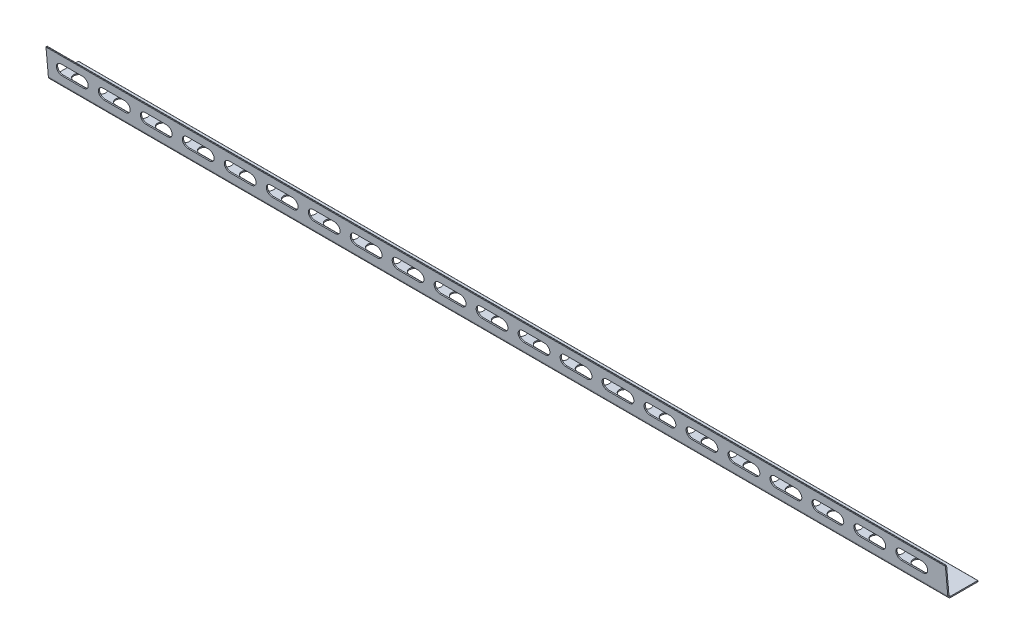
SolidWorks part; units mm, degrees
ref_plane "前视基准面" through (0, 0, 0) normal (0, 0, 1) x (1, 0, 0)
ref_plane "上视基准面" through (0, 0, 0) normal (0, 1, 0) x (1, 0, 0)
ref_plane "右视基准面" through (0, 0, 0) normal (1, 0, 0) x (0, 0, -1)
other "Configuration Table"
sketch "草图1" plane through (0, 0, 0) normal (1, 0, 0) x (0, 0, -1)
  line L0 (-0.5, 0) -> (-45.4183, 0)
  line L1 (-50.3993, 4.5642) -> (-54.3142, 49.3116)
  line L2 (-0.5, 2) -> (-45.4183, 2)
  line L3 (-48.4069, 4.7385) -> (-52.3218, 49.4859)
  line L4 (-53.8597, 49.8533) -> (-52.8635, 49.9405)
  line L5 (-48.4069, 4.7385) -> (-52.3654, 49.984) construction
  line L6 (-50.3993, 4.5642) -> (-54.3578, 49.8097) construction
  line L7 (0, 0.5) -> (0, 1.5)
  line L8 (0, 0) -> (-45.4183, 0) construction
  line L9 (0, 2) -> (-45.4183, 2) construction
  arc A0 (-50.3993, 4.5642) -> (-45.4183, 0) centre (-45.4183, 5) ccw
  arc A1 (-48.4069, 4.7385) -> (-45.4183, 2) centre (-45.4183, 5) ccw
  arc A2 (-52.8635, 49.9405) -> (-52.3218, 49.4859) centre (-52.8199, 49.4424) cw
  arc A3 (-53.8597, 49.8533) -> (-54.3142, 49.3116) centre (-53.8161, 49.3552) ccw
  arc A4 (0, 0.5) -> (-0.5, 0) centre (-0.5, 0.5) cw
  arc A5 (0, 1.5) -> (-0.5, 2) centre (-0.5, 1.5) ccw
  point P6 (-50, 0)
  point P18 (-54.3578, 49.8097)
  point P22 (0, 0)
  dimension "D4" = 5
  dimension "D6" = 0.5
  dimension "D7" = 0.5
  dimension "D1" = 50
  dimension "D2" = 50
  dimension "D3" = 95
  dimension "D5" = 2
extrude "凸台-拉伸1" add sketch "草图1" along normal blind 1500
sketch "草图2" plane through (0, 2, 0) normal (0, 1, 0) x (1, 0, 0)
  line L0 (24.5, -23.5) -> (59.5, -23.5) construction
  line L1 (24.5, -14.5) -> (59.5, -14.5)
  line L2 (24.5, -32.5) -> (59.5, -32.5)
  line L3 (0, -0.5) -> (0, -45.4183) construction
  line L4 (1500, -0.5) -> (0, -0.5) construction
  line L5 (94.5, -23.5) -> (129.5, -23.5) construction
  line L6 (94.5, -14.5) -> (129.5, -14.5)
  line L7 (94.5, -32.5) -> (129.5, -32.5)
  line L8 (164.5, -23.5) -> (199.5, -23.5) construction
  line L9 (164.5, -14.5) -> (199.5, -14.5)
  line L10 (164.5, -32.5) -> (199.5, -32.5)
  line L11 (234.5, -23.5) -> (269.5, -23.5) construction
  line L12 (234.5, -14.5) -> (269.5, -14.5)
  line L13 (234.5, -32.5) -> (269.5, -32.5)
  line L14 (304.5, -23.5) -> (339.5, -23.5) construction
  line L15 (304.5, -14.5) -> (339.5, -14.5)
  line L16 (304.5, -32.5) -> (339.5, -32.5)
  line L17 (374.5, -23.5) -> (409.5, -23.5) construction
  line L18 (374.5, -14.5) -> (409.5, -14.5)
  line L19 (374.5, -32.5) -> (409.5, -32.5)
  line L20 (444.5, -23.5) -> (479.5, -23.5) construction
  line L21 (444.5, -14.5) -> (479.5, -14.5)
  line L22 (444.5, -32.5) -> (479.5, -32.5)
  line L23 (514.5, -23.5) -> (549.5, -23.5) construction
  line L24 (514.5, -14.5) -> (549.5, -14.5)
  line L25 (514.5, -32.5) -> (549.5, -32.5)
  line L26 (584.5, -23.5) -> (619.5, -23.5) construction
  line L27 (584.5, -14.5) -> (619.5, -14.5)
  line L28 (584.5, -32.5) -> (619.5, -32.5)
  line L29 (654.5, -23.5) -> (689.5, -23.5) construction
  line L30 (654.5, -14.5) -> (689.5, -14.5)
  line L31 (654.5, -32.5) -> (689.5, -32.5)
  line L32 (724.5, -23.5) -> (759.5, -23.5) construction
  line L33 (724.5, -14.5) -> (759.5, -14.5)
  line L34 (724.5, -32.5) -> (759.5, -32.5)
  line L35 (794.5, -23.5) -> (829.5, -23.5) construction
  line L36 (794.5, -14.5) -> (829.5, -14.5)
  line L37 (794.5, -32.5) -> (829.5, -32.5)
  line L38 (864.5, -23.5) -> (899.5, -23.5) construction
  line L39 (864.5, -14.5) -> (899.5, -14.5)
  line L40 (864.5, -32.5) -> (899.5, -32.5)
  line L41 (934.5, -23.5) -> (969.5, -23.5) construction
  line L42 (934.5, -14.5) -> (969.5, -14.5)
  line L43 (934.5, -32.5) -> (969.5, -32.5)
  line L44 (1004.5, -23.5) -> (1039.5, -23.5) construction
  line L45 (1004.5, -14.5) -> (1039.5, -14.5)
  line L46 (1004.5, -32.5) -> (1039.5, -32.5)
  line L47 (1074.5, -23.5) -> (1109.5, -23.5) construction
  line L48 (1074.5, -14.5) -> (1109.5, -14.5)
  line L49 (1074.5, -32.5) -> (1109.5, -32.5)
  line L50 (1144.5, -23.5) -> (1179.5, -23.5) construction
  line L51 (1144.5, -14.5) -> (1179.5, -14.5)
  line L52 (1144.5, -32.5) -> (1179.5, -32.5)
  line L53 (1214.5, -23.5) -> (1249.5, -23.5) construction
  line L54 (1214.5, -14.5) -> (1249.5, -14.5)
  line L55 (1214.5, -32.5) -> (1249.5, -32.5)
  line L56 (1284.5, -23.5) -> (1319.5, -23.5) construction
  line L57 (1284.5, -14.5) -> (1319.5, -14.5)
  line L58 (1284.5, -32.5) -> (1319.5, -32.5)
  line L59 (1354.5, -23.5) -> (1389.5, -23.5) construction
  line L60 (1354.5, -14.5) -> (1389.5, -14.5)
  line L61 (1354.5, -32.5) -> (1389.5, -32.5)
  line L62 (1424.5, -23.5) -> (1459.5, -23.5) construction
  line L63 (1424.5, -14.5) -> (1459.5, -14.5)
  line L64 (1424.5, -32.5) -> (1459.5, -32.5)
  line L65 (0, -45.4183) -> (0, -53.1914)
  arc A0 (24.5, -14.5) -> (24.5, -32.5) centre (24.5, -23.5) ccw
  arc A1 (59.5, -32.5) -> (59.5, -14.5) centre (59.5, -23.5) ccw
  arc A2 (94.5, -14.5) -> (94.5, -32.5) centre (94.5, -23.5) ccw
  arc A3 (129.5, -32.5) -> (129.5, -14.5) centre (129.5, -23.5) ccw
  arc A4 (164.5, -14.5) -> (164.5, -32.5) centre (164.5, -23.5) ccw
  arc A5 (199.5, -32.5) -> (199.5, -14.5) centre (199.5, -23.5) ccw
  arc A6 (234.5, -14.5) -> (234.5, -32.5) centre (234.5, -23.5) ccw
  arc A7 (269.5, -32.5) -> (269.5, -14.5) centre (269.5, -23.5) ccw
  arc A8 (304.5, -14.5) -> (304.5, -32.5) centre (304.5, -23.5) ccw
  arc A9 (339.5, -32.5) -> (339.5, -14.5) centre (339.5, -23.5) ccw
  arc A10 (374.5, -14.5) -> (374.5, -32.5) centre (374.5, -23.5) ccw
  arc A11 (409.5, -32.5) -> (409.5, -14.5) centre (409.5, -23.5) ccw
  arc A12 (444.5, -14.5) -> (444.5, -32.5) centre (444.5, -23.5) ccw
  arc A13 (479.5, -32.5) -> (479.5, -14.5) centre (479.5, -23.5) ccw
  arc A14 (514.5, -14.5) -> (514.5, -32.5) centre (514.5, -23.5) ccw
  arc A15 (549.5, -32.5) -> (549.5, -14.5) centre (549.5, -23.5) ccw
  arc A16 (584.5, -14.5) -> (584.5, -32.5) centre (584.5, -23.5) ccw
  arc A17 (619.5, -32.5) -> (619.5, -14.5) centre (619.5, -23.5) ccw
  arc A18 (654.5, -14.5) -> (654.5, -32.5) centre (654.5, -23.5) ccw
  arc A19 (689.5, -32.5) -> (689.5, -14.5) centre (689.5, -23.5) ccw
  arc A20 (724.5, -14.5) -> (724.5, -32.5) centre (724.5, -23.5) ccw
  arc A21 (759.5, -32.5) -> (759.5, -14.5) centre (759.5, -23.5) ccw
  arc A22 (794.5, -14.5) -> (794.5, -32.5) centre (794.5, -23.5) ccw
  arc A23 (829.5, -32.5) -> (829.5, -14.5) centre (829.5, -23.5) ccw
  arc A24 (864.5, -14.5) -> (864.5, -32.5) centre (864.5, -23.5) ccw
  arc A25 (899.5, -32.5) -> (899.5, -14.5) centre (899.5, -23.5) ccw
  arc A26 (934.5, -14.5) -> (934.5, -32.5) centre (934.5, -23.5) ccw
  arc A27 (969.5, -32.5) -> (969.5, -14.5) centre (969.5, -23.5) ccw
  arc A28 (1004.5, -14.5) -> (1004.5, -32.5) centre (1004.5, -23.5) ccw
  arc A29 (1039.5, -32.5) -> (1039.5, -14.5) centre (1039.5, -23.5) ccw
  arc A30 (1074.5, -14.5) -> (1074.5, -32.5) centre (1074.5, -23.5) ccw
  arc A31 (1109.5, -32.5) -> (1109.5, -14.5) centre (1109.5, -23.5) ccw
  arc A32 (1144.5, -14.5) -> (1144.5, -32.5) centre (1144.5, -23.5) ccw
  arc A33 (1179.5, -32.5) -> (1179.5, -14.5) centre (1179.5, -23.5) ccw
  arc A34 (1214.5, -14.5) -> (1214.5, -32.5) centre (1214.5, -23.5) ccw
  arc A35 (1249.5, -32.5) -> (1249.5, -14.5) centre (1249.5, -23.5) ccw
  arc A36 (1284.5, -14.5) -> (1284.5, -32.5) centre (1284.5, -23.5) ccw
  arc A37 (1319.5, -32.5) -> (1319.5, -14.5) centre (1319.5, -23.5) ccw
  arc A38 (1354.5, -14.5) -> (1354.5, -32.5) centre (1354.5, -23.5) ccw
  arc A39 (1389.5, -32.5) -> (1389.5, -14.5) centre (1389.5, -23.5) ccw
  arc A40 (1424.5, -14.5) -> (1424.5, -32.5) centre (1424.5, -23.5) ccw
  arc A41 (1459.5, -32.5) -> (1459.5, -14.5) centre (1459.5, -23.5) ccw
  point P2 (42, -23.5)
  point P9 (0, -22.9592)
  point P15 (112, -23.5)
  point P22 (182, -23.5)
  point P29 (252, -23.5)
  point P36 (322, -23.5)
  point P43 (392, -23.5)
  point P50 (462, -23.5)
  point P57 (532, -23.5)
  point P64 (602, -23.5)
  point P71 (672, -23.5)
  point P78 (742, -23.5)
  point P85 (812, -23.5)
  point P92 (882, -23.5)
  point P99 (952, -23.5)
  point P106 (1022, -23.5)
  point P113 (1092, -23.5)
  point P120 (1162, -23.5)
  point P127 (1232, -23.5)
  point P134 (1302, -23.5)
  point P141 (1372, -23.5)
  point P148 (1442, -23.5)
  dimension "D1" = 24.5
  dimension "D4" = 14
  dimension "D2" = 9
  dimension "D3" = 35
  dimension "D5" = 21
sketch "草图3" plane through (0, -4.1669, 47.6278) normal (0, 0.0872, -0.9962) x (-1, 0, 0)
  line L0 (-59.5, 31.9394) -> (-24.5, 31.9394) construction
  line L1 (-59.5, 40.9394) -> (-24.5, 40.9394)
  line L2 (-59.5, 22.9394) -> (-24.5, 22.9394)
  line L3 (0, 8.9394) -> (0, 53.8578) construction
  line L4 (-1500, 8.9394) -> (0, 8.9394) construction
  line L5 (-129.5, 31.9394) -> (-94.5, 31.9394) construction
  line L6 (-129.5, 40.9394) -> (-94.5, 40.9394)
  line L7 (-129.5, 22.9394) -> (-94.5, 22.9394)
  line L8 (-199.5, 31.9394) -> (-164.5, 31.9394) construction
  line L9 (-199.5, 40.9394) -> (-164.5, 40.9394)
  line L10 (-199.5, 22.9394) -> (-164.5, 22.9394)
  line L11 (-269.5, 31.9394) -> (-234.5, 31.9394) construction
  line L12 (-269.5, 40.9394) -> (-234.5, 40.9394)
  line L13 (-269.5, 22.9394) -> (-234.5, 22.9394)
  line L14 (-339.5, 31.9394) -> (-304.5, 31.9394) construction
  line L15 (-339.5, 40.9394) -> (-304.5, 40.9394)
  line L16 (-339.5, 22.9394) -> (-304.5, 22.9394)
  line L17 (-409.5, 31.9394) -> (-374.5, 31.9394) construction
  line L18 (-409.5, 40.9394) -> (-374.5, 40.9394)
  line L19 (-409.5, 22.9394) -> (-374.5, 22.9394)
  line L20 (-479.5, 31.9394) -> (-444.5, 31.9394) construction
  line L21 (-479.5, 40.9394) -> (-444.5, 40.9394)
  line L22 (-479.5, 22.9394) -> (-444.5, 22.9394)
  line L23 (-549.5, 31.9394) -> (-514.5, 31.9394) construction
  line L24 (-549.5, 40.9394) -> (-514.5, 40.9394)
  line L25 (-549.5, 22.9394) -> (-514.5, 22.9394)
  line L26 (-619.5, 31.9394) -> (-584.5, 31.9394) construction
  line L27 (-619.5, 40.9394) -> (-584.5, 40.9394)
  line L28 (-619.5, 22.9394) -> (-584.5, 22.9394)
  line L29 (-689.5, 31.9394) -> (-654.5, 31.9394) construction
  line L30 (-689.5, 40.9394) -> (-654.5, 40.9394)
  line L31 (-689.5, 22.9394) -> (-654.5, 22.9394)
  line L32 (-759.5, 31.9394) -> (-724.5, 31.9394) construction
  line L33 (-759.5, 40.9394) -> (-724.5, 40.9394)
  line L34 (-759.5, 22.9394) -> (-724.5, 22.9394)
  line L35 (-829.5, 31.9394) -> (-794.5, 31.9394) construction
  line L36 (-829.5, 40.9394) -> (-794.5, 40.9394)
  line L37 (-829.5, 22.9394) -> (-794.5, 22.9394)
  line L38 (-899.5, 31.9394) -> (-864.5, 31.9394) construction
  line L39 (-899.5, 40.9394) -> (-864.5, 40.9394)
  line L40 (-899.5, 22.9394) -> (-864.5, 22.9394)
  line L41 (-969.5, 31.9394) -> (-934.5, 31.9394) construction
  line L42 (-969.5, 40.9394) -> (-934.5, 40.9394)
  line L43 (-969.5, 22.9394) -> (-934.5, 22.9394)
  line L44 (-1039.5, 31.9394) -> (-1004.5, 31.9394) construction
  line L45 (-1039.5, 40.9394) -> (-1004.5, 40.9394)
  line L46 (-1039.5, 22.9394) -> (-1004.5, 22.9394)
  line L47 (-1109.5, 31.9394) -> (-1074.5, 31.9394) construction
  line L48 (-1109.5, 40.9394) -> (-1074.5, 40.9394)
  line L49 (-1109.5, 22.9394) -> (-1074.5, 22.9394)
  line L50 (-1179.5, 31.9394) -> (-1144.5, 31.9394) construction
  line L51 (-1179.5, 40.9394) -> (-1144.5, 40.9394)
  line L52 (-1179.5, 22.9394) -> (-1144.5, 22.9394)
  line L53 (-1249.5, 31.9394) -> (-1214.5, 31.9394) construction
  line L54 (-1249.5, 40.9394) -> (-1214.5, 40.9394)
  line L55 (-1249.5, 22.9394) -> (-1214.5, 22.9394)
  line L56 (-1319.5, 31.9394) -> (-1284.5, 31.9394) construction
  line L57 (-1319.5, 40.9394) -> (-1284.5, 40.9394)
  line L58 (-1319.5, 22.9394) -> (-1284.5, 22.9394)
  line L59 (-1389.5, 31.9394) -> (-1354.5, 31.9394) construction
  line L60 (-1389.5, 40.9394) -> (-1354.5, 40.9394)
  line L61 (-1389.5, 22.9394) -> (-1354.5, 22.9394)
  line L62 (-1459.5, 31.9394) -> (-1424.5, 31.9394) construction
  line L63 (-1459.5, 40.9394) -> (-1424.5, 40.9394)
  line L64 (-1459.5, 22.9394) -> (-1424.5, 22.9394)
  arc A0 (-59.5, 40.9394) -> (-59.5, 22.9394) centre (-59.5, 31.9394) ccw
  arc A1 (-24.5, 22.9394) -> (-24.5, 40.9394) centre (-24.5, 31.9394) ccw
  arc A2 (-129.5, 40.9394) -> (-129.5, 22.9394) centre (-129.5, 31.9394) ccw
  arc A3 (-94.5, 22.9394) -> (-94.5, 40.9394) centre (-94.5, 31.9394) ccw
  arc A4 (-199.5, 40.9394) -> (-199.5, 22.9394) centre (-199.5, 31.9394) ccw
  arc A5 (-164.5, 22.9394) -> (-164.5, 40.9394) centre (-164.5, 31.9394) ccw
  arc A6 (-269.5, 40.9394) -> (-269.5, 22.9394) centre (-269.5, 31.9394) ccw
  arc A7 (-234.5, 22.9394) -> (-234.5, 40.9394) centre (-234.5, 31.9394) ccw
  arc A8 (-339.5, 40.9394) -> (-339.5, 22.9394) centre (-339.5, 31.9394) ccw
  arc A9 (-304.5, 22.9394) -> (-304.5, 40.9394) centre (-304.5, 31.9394) ccw
  arc A10 (-409.5, 40.9394) -> (-409.5, 22.9394) centre (-409.5, 31.9394) ccw
  arc A11 (-374.5, 22.9394) -> (-374.5, 40.9394) centre (-374.5, 31.9394) ccw
  arc A12 (-479.5, 40.9394) -> (-479.5, 22.9394) centre (-479.5, 31.9394) ccw
  arc A13 (-444.5, 22.9394) -> (-444.5, 40.9394) centre (-444.5, 31.9394) ccw
  arc A14 (-549.5, 40.9394) -> (-549.5, 22.9394) centre (-549.5, 31.9394) ccw
  arc A15 (-514.5, 22.9394) -> (-514.5, 40.9394) centre (-514.5, 31.9394) ccw
  arc A16 (-619.5, 40.9394) -> (-619.5, 22.9394) centre (-619.5, 31.9394) ccw
  arc A17 (-584.5, 22.9394) -> (-584.5, 40.9394) centre (-584.5, 31.9394) ccw
  arc A18 (-689.5, 40.9394) -> (-689.5, 22.9394) centre (-689.5, 31.9394) ccw
  arc A19 (-654.5, 22.9394) -> (-654.5, 40.9394) centre (-654.5, 31.9394) ccw
  arc A20 (-759.5, 40.9394) -> (-759.5, 22.9394) centre (-759.5, 31.9394) ccw
  arc A21 (-724.5, 22.9394) -> (-724.5, 40.9394) centre (-724.5, 31.9394) ccw
  arc A22 (-829.5, 40.9394) -> (-829.5, 22.9394) centre (-829.5, 31.9394) ccw
  arc A23 (-794.5, 22.9394) -> (-794.5, 40.9394) centre (-794.5, 31.9394) ccw
  arc A24 (-899.5, 40.9394) -> (-899.5, 22.9394) centre (-899.5, 31.9394) ccw
  arc A25 (-864.5, 22.9394) -> (-864.5, 40.9394) centre (-864.5, 31.9394) ccw
  arc A26 (-969.5, 40.9394) -> (-969.5, 22.9394) centre (-969.5, 31.9394) ccw
  arc A27 (-934.5, 22.9394) -> (-934.5, 40.9394) centre (-934.5, 31.9394) ccw
  arc A28 (-1039.5, 40.9394) -> (-1039.5, 22.9394) centre (-1039.5, 31.9394) ccw
  arc A29 (-1004.5, 22.9394) -> (-1004.5, 40.9394) centre (-1004.5, 31.9394) ccw
  arc A30 (-1109.5, 40.9394) -> (-1109.5, 22.9394) centre (-1109.5, 31.9394) ccw
  arc A31 (-1074.5, 22.9394) -> (-1074.5, 40.9394) centre (-1074.5, 31.9394) ccw
  arc A32 (-1179.5, 40.9394) -> (-1179.5, 22.9394) centre (-1179.5, 31.9394) ccw
  arc A33 (-1144.5, 22.9394) -> (-1144.5, 40.9394) centre (-1144.5, 31.9394) ccw
  arc A34 (-1249.5, 40.9394) -> (-1249.5, 22.9394) centre (-1249.5, 31.9394) ccw
  arc A35 (-1214.5, 22.9394) -> (-1214.5, 40.9394) centre (-1214.5, 31.9394) ccw
  arc A36 (-1319.5, 40.9394) -> (-1319.5, 22.9394) centre (-1319.5, 31.9394) ccw
  arc A37 (-1284.5, 22.9394) -> (-1284.5, 40.9394) centre (-1284.5, 31.9394) ccw
  arc A38 (-1389.5, 40.9394) -> (-1389.5, 22.9394) centre (-1389.5, 31.9394) ccw
  arc A39 (-1354.5, 22.9394) -> (-1354.5, 40.9394) centre (-1354.5, 31.9394) ccw
  arc A40 (-1459.5, 40.9394) -> (-1459.5, 22.9394) centre (-1459.5, 31.9394) ccw
  arc A41 (-1424.5, 22.9394) -> (-1424.5, 40.9394) centre (-1424.5, 31.9394) ccw
  point P2 (-42, 31.9394)
  point P15 (-112, 31.9394)
  point P22 (-182, 31.9394)
  point P29 (-252, 31.9394)
  point P36 (-322, 31.9394)
  point P43 (-392, 31.9394)
  point P50 (-462, 31.9394)
  point P57 (-532, 31.9394)
  point P64 (-602, 31.9394)
  point P71 (-672, 31.9394)
  point P78 (-742, 31.9394)
  point P85 (-812, 31.9394)
  point P92 (-882, 31.9394)
  point P99 (-952, 31.9394)
  point P106 (-1022, 31.9394)
  point P113 (-1092, 31.9394)
  point P120 (-1162, 31.9394)
  point P127 (-1232, 31.9394)
  point P134 (-1302, 31.9394)
  point P141 (-1372, 31.9394)
  point P148 (-1442, 31.9394)
  dimension "D1" = 9
  dimension "D2" = 24.5
  dimension "D3" = 35
  dimension "D4" = 14
  dimension "D5" = 21
extrude "切除-拉伸3" cut sketch "草图3" against normal through all
extrude "切除-拉伸5" cut sketch "草图2" against normal through all contours L1 A1 L2 A0 | L6 A3 L7 A2 | L9 A5 L10 A4 | L12 A7 L13 A6 | L15 A9 L16 A8 | L18 A11 L19 A10 | L21 A13 L22 A12 | L24 A15 L25 A14 | L27 A17 L28 A16 | L30 A19 L31 A18 | L33 A21 L34 A20 | L36 A23 L37 A22 | L39 A25 L40 A24 | L42 A27 L43 A26 | L45 A29 L46 A28 | L48 A31 L49 A30 | L51 A33 L52 A32 | L54 A35 L55 A34 | L57 A37 L58 A36 | L60 A39 L61 A38 | L63 A41 L64 A40
